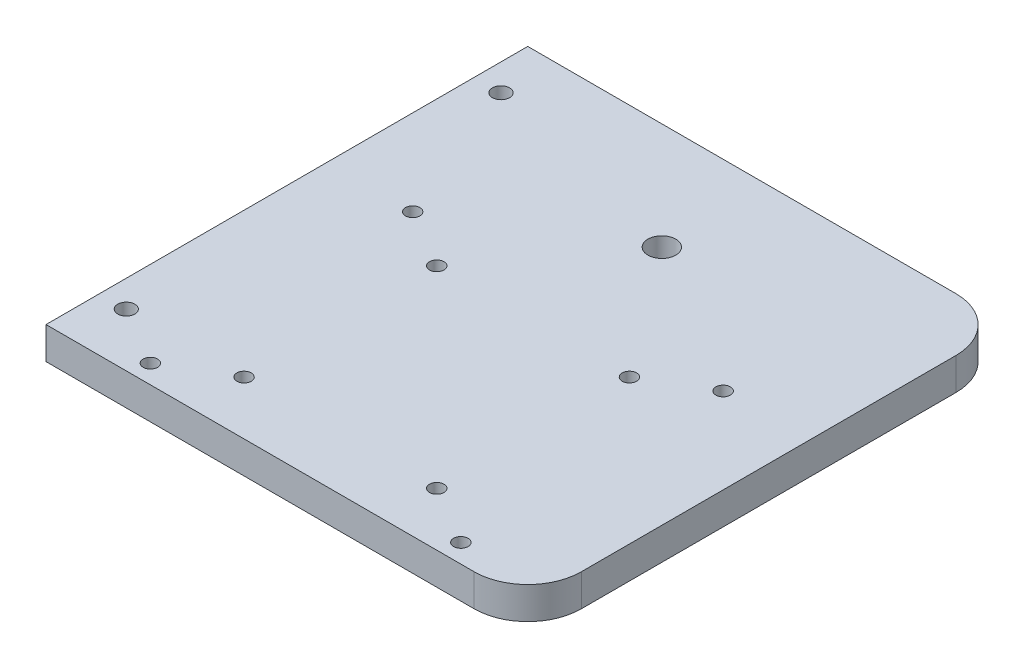
SolidWorks part; units mm, degrees
material "Thornel Mat VMA"
ref_plane "前视基准面" through (0, 0, 0) normal (0, 0, 1) x (1, 0, 0)
ref_plane "上视基准面" through (0, 0, 0) normal (0, 1, 0) x (1, 0, 0)
ref_plane "右视基准面" through (0, 0, 0) normal (1, 0, 0) x (0, 0, -1)
other "Configuration Table"
sketch "草图1" plane through (0, 0, 0) normal (0, 1, 0) x (1, 0, 0)
  line L1 (-45, -45) -> (45, -45)
  line L2 (-45, -45) -> (-45, 45)
  line L3 (-45, 45) -> (45, 45)
  line L4 (45, -45) -> (45, 45)
  line L5 (-45, -45) -> (45, 45) construction
  line L6 (-45, 45) -> (45, -45) construction
  point P0 (0, 0)
  dimension "D1" = 90
  dimension "D2" = 90
extrude "凸台-拉伸1" add sketch "草图1" along normal blind 6
sketch "草图2" plane through (0, 6, 0) normal (0, 1, 0) x (1, 0, 0)
  line L0 (0, 55.815) -> (0, -56.5084) construction
  line L1 (-45, -45) -> (45, -45) construction
  line L2 (-29, 7.5) -> (-29, -41.5) construction
  line L3 (-29, -17) -> (5.3791, -17) construction
  circle A0 centre (-29, 7.5) radius 1.35
  circle A1 centre (-29, -41.5) radius 1.35
  circle A2 centre (-18, 1) radius 1.35
  circle A3 centre (-18, -35) radius 1.35
  circle A4 centre (18, -35) radius 1.35
  circle A5 centre (29, -41.5) radius 1.35
  circle A6 centre (18, 1) radius 1.35
  circle A7 centre (29, 7.5) radius 1.35
  dimension "D1" = 2.7
  dimension "D2" = 2.7
  dimension "D5" = 2.7
  dimension "D7" = 36
  dimension "D8" = 58
  dimension "D3" = 3.5
  dimension "D4" = 49
  dimension "D6" = 36
extrude "切除-拉伸1" cut sketch "草图2" against normal up to surface (6 mm away) up to face at (0, 0, 0)
sketch "草图3" plane through (0, 6, 0) normal (0, 1, 0) x (1, 0, 0)
  line L4 (45, -45) -> (45, 45)
  line L5 (45, 45) -> (-45, 45)
  line L6 (-45, 45) -> (-45, -45)
  line L7 (-45, -45) -> (45, -45)
  line L8 (45, -45) -> (45, 45) construction
  line L9 (45, 45) -> (-45, 45) construction
  line L10 (-45, 45) -> (-45, -45) construction
  line L11 (-45, -45) -> (45, -45) construction
  circle A0 centre (0, 25.05) radius 2.6
  dimension "D2" = 5.2
  dimension "D3" = 19.95
  dimension "D1" = 0
extrude "切除-拉伸2" cut sketch "草图3" against normal up to surface (6 mm away) up to face at (18, 0, 33.65)
sketch "草图4" plane through (0, 6, 0) normal (0, 1, 0) x (1, 0, 0)
  line L0 (-45, 0) -> (-6.8114, 0) construction
  line L4 (45, -45) -> (45, 45)
  line L5 (45, 45) -> (-45, 45)
  line L6 (-45, 45) -> (-45, -45)
  line L7 (-45, -45) -> (45, -45)
  line L8 (45, -45) -> (45, 45) construction
  line L9 (45, 45) -> (-45, 45) construction
  line L10 (-45, 45) -> (-45, -45) construction
  line L11 (-45, -45) -> (45, -45) construction
  circle A0 centre (-40, -35) radius 1.6
  circle A1 centre (-40, 35) radius 1.6
  dimension "D4" = 3.2
  dimension "D2" = 5
  dimension "D3" = 10
  dimension "D1" = 0
extrude "切除-拉伸3" cut sketch "草图4" against normal up to surface (6 mm away) up to face at (0, 0, -27.65)
fillet "圆角1" radius 10 2 edges at (45, 3, 45) (45, 3, -45)
